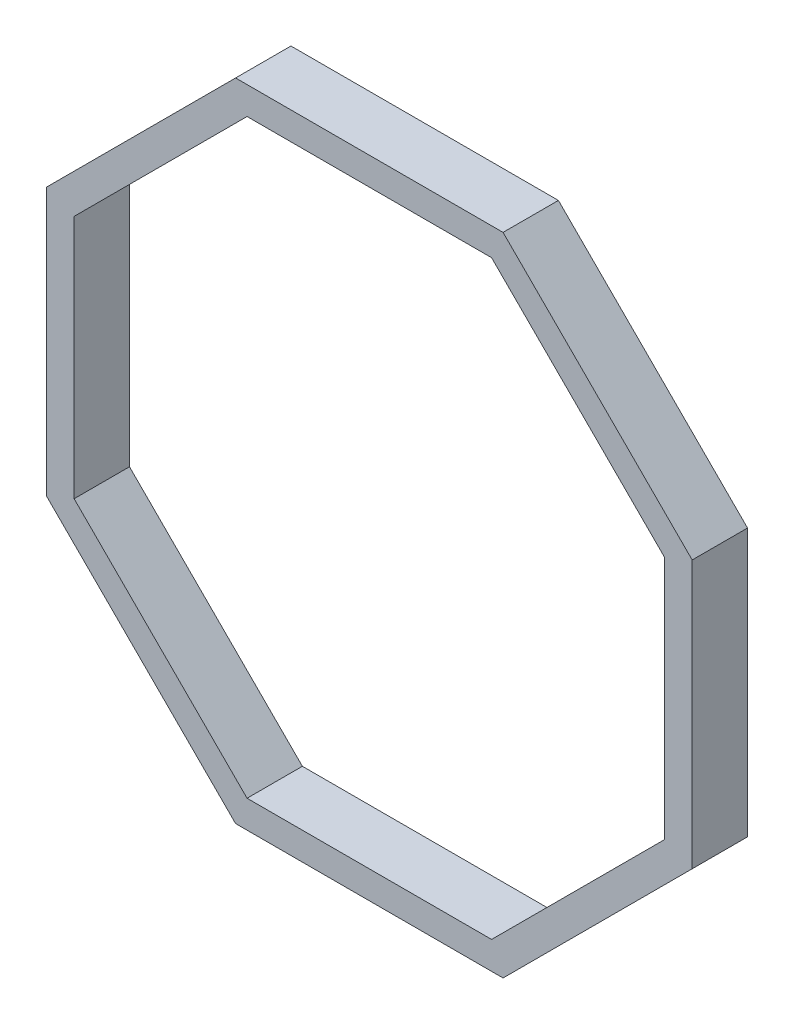
SolidWorks part; units mm, degrees
ref_plane "Plano frontal" through (0, 0, 0) normal (0, 0, 1) x (1, 0, 0)
ref_plane "Plano superior" through (0, 0, 0) normal (0, 1, 0) x (1, 0, 0)
ref_plane "Plano direito" through (0, 0, 0) normal (1, 0, 0) x (0, 0, -1)
sketch "Esboço1" plane through (0, 0, 0) normal (0, 0, 1) x (1, 0, 0)
  line L9 (175, 72.4874) -> (72.4874, 175)
  line L10 (72.4874, 175) -> (-72.4874, 175)
  line L11 (-72.4874, 175) -> (-175, 72.4874)
  line L12 (-175, 72.4874) -> (-175, -72.4874)
  line L13 (-175, -72.4874) -> (-72.4874, -175)
  line L14 (-72.4874, -175) -> (72.4874, -175)
  line L15 (72.4874, -175) -> (175, -72.4874)
  line L16 (175, -72.4874) -> (175, 72.4874)
  line L17 (160, 66.2742) -> (66.2742, 160)
  line L18 (66.2742, 160) -> (-66.2742, 160)
  line L19 (-66.2742, 160) -> (-160, 66.2742)
  line L20 (-160, 66.2742) -> (-160, -66.2742)
  line L21 (-160, -66.2742) -> (-66.2742, -160)
  line L22 (-66.2742, -160) -> (66.2742, -160)
  line L23 (66.2742, -160) -> (160, -66.2742)
  line L24 (160, -66.2742) -> (160, 66.2742)
  circle A0 centre (0, 0) radius 175 construction
  circle A1 centre (0, 0) radius 160 construction
extrude "Ressalto-extrusão1" add sketch "Esboço1" along normal blind 30
